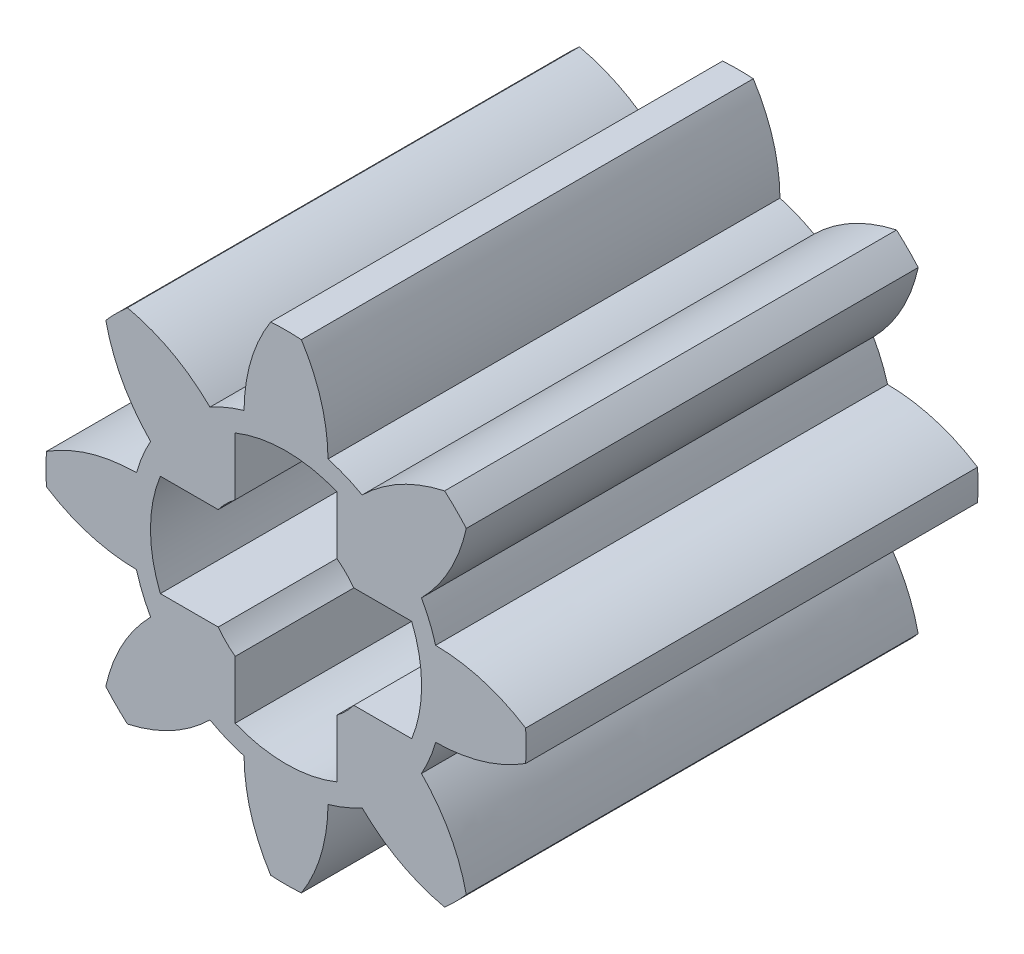
SolidWorks part; units mm, degrees
ref_plane "Front Plane" through (0, 0, 0) normal (0, 0, 1) x (1, 0, 0)
ref_plane "Top Plane" through (0, 0, 0) normal (0, 1, 0) x (1, 0, 0)
ref_plane "Right Plane" through (0, 0, 0) normal (1, 0, 0) x (0, 0, -1)
sketch "Sketch1" plane through (0, 0, 0) normal (0, 0, 1) x (1, 0, 0)
  circle A0 centre (0, 0) radius 2.75
  circle A1 centre (0, 0) radius 1.5
  dimension "D1" = 5.5
  dimension "D2" = 3
extrude "Boss-Extrude1" add sketch "Sketch1" along normal blind 8
sketch "Sketch3" plane through (0, 0, 8) normal (0, 0, 1) x (1, 0, 0)
  line L0 (0, 0) -> (0, 7.7615) construction
  line L1 (0, 0) -> (-3.6879, 8.9033) construction
  line L2 (0, 0) -> (3.9455, 9.5252) construction
  arc A1 (0.7433, 2.6476) -> (-0.7433, 2.6476) centre (0, 0) ccw
  arc A2 (0.2715, 4.2413) -> (-0.2715, 4.2413) centre (0, 0) ccw
  spline S0 degree 2 poles (-0.2715, 4.2413) (-0.7331, 3.5139) (-0.7433, 2.6476) knots 0 0 0 1 1 1
  spline S1 degree 2 poles (0.2715, 4.2413) (0.7331, 3.5139) (0.7433, 2.6476) knots 0 0 0 1 1 1
  dimension "D1" = 8.5
  dimension "D2" = 5.5
  dimension "D3" = 22.5
  dimension "D4" = 22.5
extrude "Boss-Extrude2" add sketch "Sketch3" against normal up to surface (8 mm away) up to face at (2.75, 0, 0)
pattern_circular "CirPattern2" count 8 over 360 about axis through (0, 0, 8) along (0, 0, -1) of "Boss-Extrude2"
sketch "Sketch4" plane through (0, 0, 8) normal (0, 0, 1) x (1, 0, 0)
  line L0 (-0.9, 2.2249) -> (-0.9, 0.9)
  line L1 (0.9, 2.2249) -> (0.9, 0.9)
  line L2 (-2.2249, 0.9) -> (-0.9, 0.9)
  line L3 (-2.2249, -0.9) -> (-0.9, -0.9)
  line L4 (-0.9, -0.9) -> (-0.9, -2.2249)
  line L5 (0.9, 0.9) -> (2.2249, 0.9)
  line L6 (0.9, -0.9) -> (0.9, -2.2249)
  line L7 (0.9, -0.9) -> (2.2249, -0.9)
  arc A0 (-0.9, -2.2249) -> (0.9, -2.2249) centre (0, 0) ccw
  arc A1 (2.2249, -0.9) -> (2.2249, 0.9) centre (0, 0) ccw
  arc A2 (0.9, 2.2249) -> (-0.9, 2.2249) centre (0, 0) ccw
  arc A3 (-2.2249, 0.9) -> (-2.2249, -0.9) centre (0, 0) ccw
  dimension "D1" = 4.8
  dimension "D2" = 0.9
  dimension "D3" = 0.9
  dimension "D4" = 0.9
extrude "Cut-Extrude1" cut sketch "Sketch4" against normal blind 10
